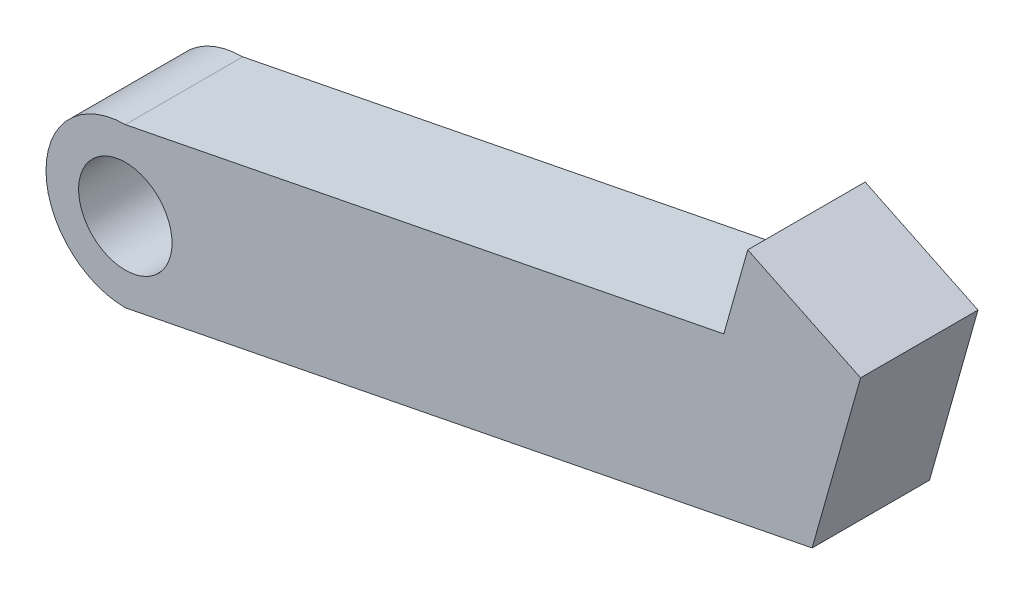
SolidWorks part; units mm, degrees
material "1060 Alloy"
ref_plane "Front Plane" through (0, 0, 0) normal (0, 0, 1) x (1, 0, 0)
ref_plane "Top Plane" through (0, 0, 0) normal (0, 1, 0) x (1, 0, 0)
ref_plane "Right Plane" through (0, 0, 0) normal (1, 0, 0) x (0, 0, -1)
sketch "Sketch1" plane through (0, 0, 0) normal (0, 0, 1) x (1, 0, 0)
  line L0 (0, -55) -> (0, 55) construction
  line L1 (0, -5.715) -> (49.4788, 4.0389)
  line L3 (49.4788, 4.0389) -> (52.9706, 16.4)
  line L4 (52.9706, 16.4) -> (44.8416, 20.3253)
  line L5 (44.8416, 20.3253) -> (43.1153, 14.2144)
  line L6 (43.1153, 14.2144) -> (0, 5.715)
  circle A0 centre (0, 0) radius 3.3655
  arc A1 (0, 5.715) -> (0, -5.715) centre (0, 0) ccw
  dimension "D1" = 6.731
  dimension "D2" = 11.43
  dimension "D3" = 80
  dimension "D4" = 20.3253
  dimension "D5" = 6.35
extrude "Boss-Extrude1" add sketch "Sketch1" along normal blind 8.4582
